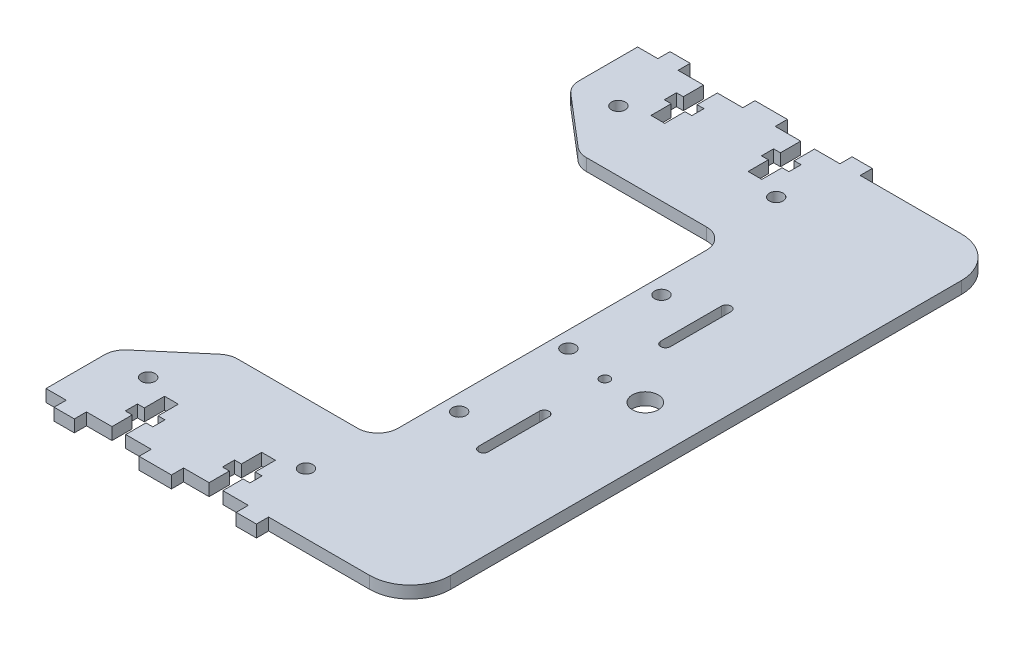
SolidWorks part; units mm, degrees
material "Thornel Mat VMA"
ref_plane "前视基准面" through (0, 0, 0) normal (0, 0, 1) x (1, 0, 0)
ref_plane "上视基准面" through (0, 0, 0) normal (0, 1, 0) x (1, 0, 0)
ref_plane "右视基准面" through (0, 0, 0) normal (1, 0, 0) x (0, 0, -1)
sketch "草图1" plane through (0, 0, 0) normal (0, 1, 0) x (1, 0, 0)
  line L0 (-25, -73.1) -> (-25, -76.1)
  line L1 (-35, -73.1) -> (-25, -73.1)
  line L2 (-35, -73.1) -> (-35, 73.1)
  line L3 (-35, 73.1) -> (-25, 73.1)
  line L4 (35, -73.1) -> (35, 73.1)
  line L5 (-35, -73.1) -> (35, 73.1) construction
  line L6 (-35, 73.1) -> (35, -73.1) construction
  line L7 (-25, -76.1) -> (-20, -76.1)
  line L8 (-20, -76.1) -> (-20, -73.1)
  line L9 (-4, -73.1) -> (-4, -76.1)
  line L10 (-4, -76.1) -> (4, -76.1)
  line L11 (4, -76.1) -> (4, -73.1)
  line L12 (20, -73.1) -> (20, -76.1)
  line L13 (20, -76.1) -> (25, -76.1)
  line L14 (25, -76.1) -> (25, -73.1)
  line L15 (-13.7, -73.1) -> (-13.7, -68.1)
  line L16 (-13.7, -68.1) -> (-15.4, -68.1)
  line L17 (-15.4, -68.1) -> (-15.4, -65.1)
  line L18 (-15.4, -65.1) -> (-13.7, -65.1)
  line L19 (-13.7, -65.1) -> (-13.7, -60.1)
  line L20 (-13.7, -60.1) -> (-10.3, -60.1)
  line L21 (-10.3, -60.1) -> (-10.3, -65.1)
  line L22 (-10.3, -65.1) -> (-8.6, -65.1)
  line L23 (-8.6, -65.1) -> (-8.6, -68.1)
  line L24 (-8.6, -68.1) -> (-10.3, -68.1)
  line L25 (-10.3, -68.1) -> (-10.3, -73.1)
  line L26 (10.3, -73.1) -> (10.3, -68.1)
  line L27 (10.3, -68.1) -> (8.6, -68.1)
  line L28 (8.6, -68.1) -> (8.6, -65.1)
  line L29 (8.6, -65.1) -> (10.3, -65.1)
  line L30 (10.3, -65.1) -> (10.3, -60.1)
  line L31 (10.3, -60.1) -> (13.7, -60.1)
  line L32 (13.7, -60.1) -> (13.7, -65.1)
  line L33 (13.7, -65.1) -> (15.4, -65.1)
  line L34 (15.4, -65.1) -> (15.4, -68.1)
  line L35 (15.4, -68.1) -> (13.7, -68.1)
  line L36 (13.7, -68.1) -> (13.7, -73.1)
  line L37 (0, 0) -> (35, 0) construction
  line L38 (-25, 73.1) -> (-25, 76.1)
  line L39 (-25, 76.1) -> (-20, 76.1)
  line L40 (-20, 76.1) -> (-20, 73.1)
  line L41 (-4, 73.1) -> (-4, 76.1)
  line L42 (-4, 76.1) -> (4, 76.1)
  line L43 (4, 76.1) -> (4, 73.1)
  line L44 (20, 73.1) -> (20, 76.1)
  line L45 (25, 76.1) -> (25, 73.1)
  line L46 (20, 76.1) -> (25, 76.1)
  line L47 (10.3, 68.1) -> (8.6, 68.1)
  line L48 (10.3, 73.1) -> (10.3, 68.1)
  line L49 (13.7, 68.1) -> (13.7, 73.1)
  line L50 (15.4, 68.1) -> (13.7, 68.1)
  line L51 (15.4, 65.1) -> (15.4, 68.1)
  line L52 (13.7, 65.1) -> (15.4, 65.1)
  line L53 (8.6, 68.1) -> (8.6, 65.1)
  line L54 (8.6, 65.1) -> (10.3, 65.1)
  line L55 (10.3, 65.1) -> (10.3, 60.1)
  line L56 (13.7, 60.1) -> (13.7, 65.1)
  line L57 (10.3, 60.1) -> (13.7, 60.1)
  line L58 (-15.4, 65.1) -> (-13.7, 65.1)
  line L59 (-15.4, 68.1) -> (-15.4, 65.1)
  line L60 (-13.7, 68.1) -> (-15.4, 68.1)
  line L61 (-13.7, 73.1) -> (-13.7, 68.1)
  line L63 (-10.3, 68.1) -> (-10.3, 73.1)
  line L64 (-8.6, 68.1) -> (-10.3, 68.1)
  line L65 (-8.6, 65.1) -> (-8.6, 68.1)
  line L66 (-10.3, 65.1) -> (-8.6, 65.1)
  line L67 (-13.7, 65.1) -> (-13.7, 60.1)
  line L68 (-10.3, 60.1) -> (-10.3, 65.1)
  line L69 (-13.7, 60.1) -> (-10.3, 60.1)
  line L70 (-20, 73.1) -> (-13.7, 73.1)
  line L71 (-10.3, 73.1) -> (-4, 73.1)
  line L72 (4, 73.1) -> (10.3, 73.1)
  line L73 (13.7, 73.1) -> (20, 73.1)
  line L74 (25, 73.1) -> (35, 73.1)
  line L75 (-20, -73.1) -> (-13.7, -73.1)
  line L77 (-10.3, -73.1) -> (-4, -73.1)
  line L79 (4, -73.1) -> (10.3, -73.1)
  line L81 (13.7, -73.1) -> (20, -73.1)
  line L83 (25, -73.1) -> (35, -73.1)
  point P0 (0, 0)
  point P32 (-12, -60.1)
  point P43 (12, -60.1)
  dimension "D1" = 70
  dimension "D2" = 146.2
  dimension "D3" = 5
  dimension "D4" = 3
  dimension "D5" = 3
  dimension "D6" = 8
  dimension "D7" = 3
  dimension "D8" = 5
  dimension "D9" = 3.4
  dimension "D10" = 3.4
  dimension "D11" = 1.7
  dimension "D12" = 1.7
  dimension "D13" = 1.7
  dimension "D14" = 1.7
  dimension "D15" = 3
  dimension "D16" = 3
  dimension "D17" = 5
  dimension "D18" = 5
  dimension "D19" = 5
  dimension "D20" = 1.7
  dimension "D21" = 1.7
  dimension "D22" = 1.7
  dimension "D23" = 1.7
  dimension "D24" = 5
  dimension "D25" = 5
  dimension "D26" = 3
  dimension "D27" = 3
  dimension "D28" = 5
  dimension "D29" = 5
  dimension "D30" = 8
  dimension "D31" = 8
  dimension "D32" = 16
  dimension "D34" = 16
extrude "凸台-拉伸1" add sketch "草图1" along normal blind 3
sketch "草图2" plane through (0, 0, 73.1) normal (0, 0, 1) x (1, 0, 0)
  line L0 (-35, 0) -> (-25, 0) construction
  line L1 (-35, 3) -> (-30, 3)
  line L2 (-35, 3) -> (-35, 0)
  line L3 (-35, 0) -> (-30, 0)
  line L4 (-30, 3) -> (-30, 0)
  line L5 (-35, 3) -> (-30, 0) construction
  line L6 (-35, 0) -> (-30, 3) construction
  point P4 (-32.5, 1.5)
  point P12 (32.5, 1.5)
  dimension "D2" = 5
extrude "切除-拉伸1" cut sketch "草图2" against normal blind 176
sketch "草图3" plane through (35, 0, 0) normal (1, 0, 0) x (0, 0, -1)
  line L4 (-73.1, 0) -> (73.1, 0)
  line L5 (73.1, 0) -> (73.1, 3)
  line L6 (73.1, 3) -> (-73.1, 3)
  line L7 (-73.1, 3) -> (-73.1, 0)
  line L8 (-73.1, 0) -> (73.1, 0)
  line L9 (73.1, 0) -> (73.1, 3)
  line L10 (73.1, 3) -> (-73.1, 3)
  line L11 (-73.1, 3) -> (-73.1, 0)
  dimension "D1" = 0
extrude "凸台-拉伸2" add sketch "草图3" along normal blind 5
sketch "草图4" plane through (0, 3, 0) normal (0, 1, 0) x (1, 0, 0)
  line L0 (-25, 73.1) -> (-30, 73.1) construction
  line L1 (-30, 73.1) -> (-30, -73.1) construction
  line L2 (40, 73.1) -> (25, 73.1) construction
  line L3 (40, 73.1) -> (40, -73.1) construction
  line L4 (-30, -73.1) -> (-25, -73.1) construction
  line L5 (25, -73.1) -> (40, -73.1) construction
  circle A0 centre (-19.75, -58.1) radius 1.7
  circle A1 centre (19.25, -58.1) radius 1.7
  circle A2 centre (19.25, 58.1) radius 1.7
  circle A3 centre (-19.75, 58.1) radius 1.7
  dimension "D1" = 3.4
  dimension "D2" = 3.4
  dimension "D3" = 3.4
  dimension "D4" = 3.4
  dimension "D5" = 15
  dimension "D6" = 10.25
  dimension "D7" = 15
  dimension "D8" = 20.75
  dimension "D9" = 15
  dimension "D10" = 10.25
  dimension "D11" = 15
  dimension "D12" = 20.75
extrude "切除-拉伸2" cut sketch "草图4" against normal blind 5
sketch "草图5" plane through (0, 3, 0) normal (0, 1, 0) x (1, 0, 0)
  line L0 (-30, -56.3314) -> (-14.5, -43.1)
  line L1 (-30, 73.1) -> (-30, -73.1) construction
  line L2 (-14.5, -43.1) -> (0, -43.1)
  line L3 (-30, 56.3314) -> (-14.5, 43.1)
  line L4 (-14.5, 43.1) -> (22, 43.1)
  line L5 (22, 43.1) -> (22, -43.1)
  line L6 (22, -43.1) -> (0, -43.1)
  line L7 (10.3, 73.1) -> (4, 73.1) construction
  line L8 (4, -73.1) -> (10.3, -73.1) construction
  line L9 (40, 73.1) -> (40, -73.1) construction
  line L10 (-30, 56.3314) -> (-30, -56.3314)
  circle A0 centre (-19.75, -58.1) radius 1.7 construction
  circle A1 centre (-19.75, 58.1) radius 1.7 construction
  dimension "D1" = 30
  dimension "D2" = 30
  dimension "D3" = 8
  dimension "D4" = 15.5
  dimension "D5" = 8
  dimension "D6" = 15.5
  dimension "D7" = 18
extrude "切除-拉伸3" cut sketch "草图5" against normal blind 10
fillet "圆角1" radius 5 6 edges at (-30, 1.5, 56.3314) (-14.5, 1.5, 43.1) (22, 1.5, 43.1) (22, 1.5, -43.1) (-14.5, 1.5, -43.1) (-30, 1.5, -56.3314)
sketch "草图7" plane through (40, 0, 0) normal (1, 0, 0) x (0, 0, -1)
  line L4 (-73.1, 3) -> (-73.1, 0)
  line L5 (-73.1, 0) -> (73.1, 0)
  line L6 (73.1, 0) -> (73.1, 3)
  line L7 (73.1, 3) -> (-73.1, 3)
  line L8 (-73.1, 3) -> (-73.1, 0)
  line L9 (-73.1, 0) -> (73.1, 0)
  line L10 (73.1, 0) -> (73.1, 3)
  line L11 (73.1, 3) -> (-73.1, 3)
  dimension "D1" = 0
extrude "凸台-拉伸3" add sketch "草图7" along normal blind 20
sketch "草图8" plane through (0, 3, 0) normal (0, 1, 0) x (1, 0, 0)
  line L0 (22, -38.1) -> (22, 38.1) construction
  line L1 (60, 73.1) -> (25, 73.1) construction
  circle A0 centre (47, -2) radius 3.2
  dimension "D1" = 6.4
  dimension "D2" = 25
  dimension "D3" = 75.1
extrude "切除-拉伸4" cut sketch "草图8" against normal blind 20
sketch "草图9" plane through (0, 3, 0) normal (0, 1, 0) x (1, 0, 0)
  line L0 (60, 73.1) -> (25, 73.1) construction
  line L1 (37, 13) -> (37, 28) construction
  line L2 (35.8, 13) -> (35.8, 28)
  line L3 (38.2, 13) -> (38.2, 28)
  line L4 (37, -17) -> (37, -32) construction
  line L5 (38.2, -17) -> (38.2, -32)
  line L6 (35.8, -17) -> (35.8, -32)
  circle A0 centre (37, -2) radius 1.2
  circle A1 centre (47, -2) radius 3.2 construction
  arc A2 (35.8, 13) -> (38.2, 13) centre (37, 13) ccw
  arc A3 (38.2, 28) -> (35.8, 28) centre (37, 28) ccw
  arc A4 (38.2, -17) -> (35.8, -17) centre (37, -17) ccw
  arc A5 (35.8, -32) -> (38.2, -32) centre (37, -32) ccw
  point P8 (37, 20.5)
  point P13 (37, -24.5)
  dimension "D1" = 2.4
  dimension "D2" = 10
  dimension "D3" = 75.1
  dimension "D6" = 15
  dimension "D7" = 15
  dimension "D8" = 1.2
  dimension "D9" = 1.2
  dimension "D4" = 15
  dimension "D5" = 15
extrude "切除-拉伸5" cut sketch "草图9" against normal blind 20
fillet "圆角2" radius 10 2 edges at (60, 1.5, 73.1) (60, 1.5, -73.1)
sketch "草图10" plane through (0, 3, 0) normal (0, 1, 0) x (1, 0, 0)
  line L0 (22, -38.1) -> (22, 38.1) construction
  circle A0 centre (26, -27) radius 1.7
  circle A1 centre (26, 23) radius 1.7
  circle A2 centre (37, -2) radius 1.2 construction
  circle A3 centre (26, 0) radius 1.7
  dimension "D1" = 3.4
  dimension "D2" = 3.4
  dimension "D3" = 25
  dimension "D4" = 25
  dimension "D5" = 3.4
  dimension "D6" = 4
  dimension "D7" = 4
  dimension "D8" = 4
extrude "切除-拉伸6" cut sketch "草图10" against normal blind 3
